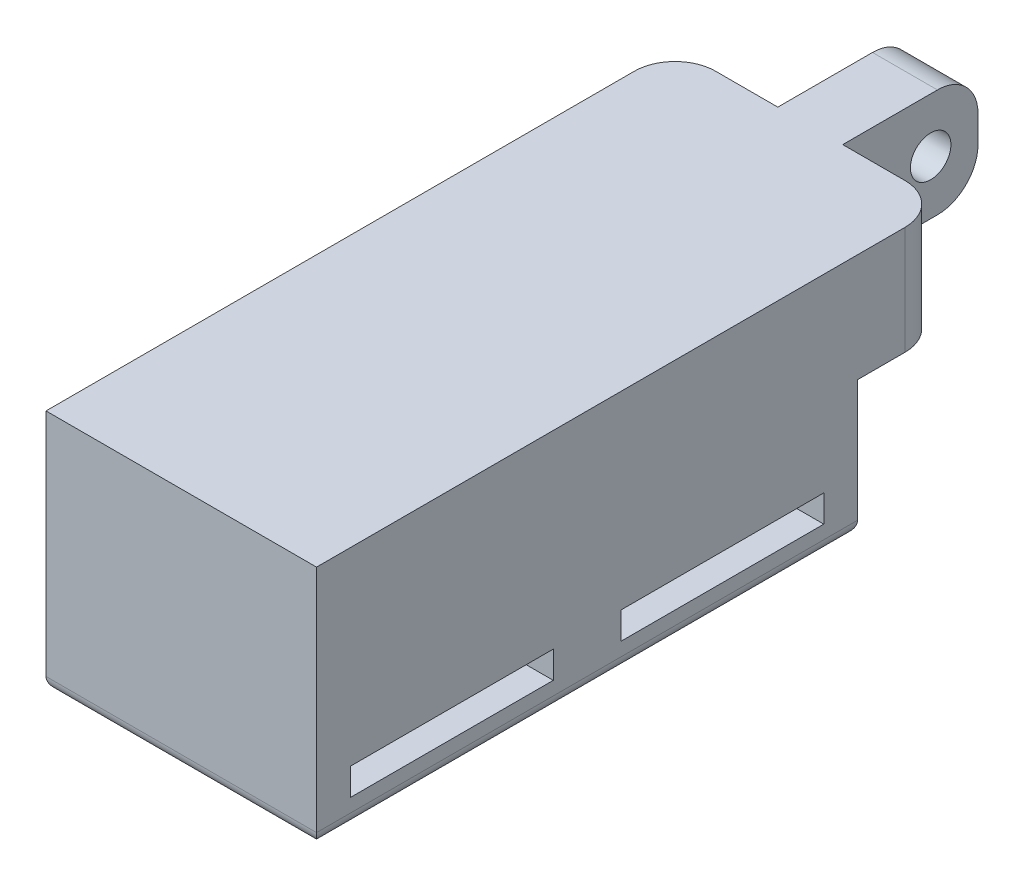
SolidWorks part; units mm, degrees
ref_plane "Alzado" through (0, 0, 0) normal (0, 0, 1) x (1, 0, 0)
ref_plane "Planta" through (0, 0, 0) normal (0, 1, 0) x (1, 0, 0)
ref_plane "Vista lateral" through (0, 0, 0) normal (1, 0, 0) x (0, 0, -1)
sketch "Croquis1" plane through (0, 0, 0) normal (1, 0, 0) x (0, 0, -1)
  line L0 (0, 9) -> (0, 1) construction
  line L9 (-1.5, 9) -> (-58, 9)
  line L18 (0, 9) -> (0, -9) construction
  line L19 (0, -9) -> (-58, -9) construction
  line L25 (0, 1) -> (-18, 1) construction
  line L26 (0, 1) -> (0, -2.6179) construction
  line L29 (0, -2.6179) -> (0, -9) construction
  line L31 (-1.5, 9) -> (-1.5, 1)
  line L32 (-18, 1) -> (-1.5, 1)
  line L35 (-58, -9) -> (-18, -9)
  line L56 (-58, 9) -> (-58, -9)
  line L59 (0, 9) -> (-58, 9) construction
  line L61 (-18, 1) -> (-18, -9)
  circle A0 centre (-5, 5) radius 1.5
  point P9 (0, 0)
  point P12 (0, 5)
  dimension "D6" = 3
  dimension "D1" = 58
  dimension "D2" = 10
  dimension "D3" = 40
  dimension "D4" = 8
  dimension "D7" = 5
  dimension "D8" = 3
extrude "Saliente-Extruir1" add sketch "Croquis1" along normal mid plane 20
sketch "Croquis2" plane through (0, 0, 0) normal (0, 1, 0) x (1, 0, 0)
  line L0 (-2.4, -11.5) -> (-10, -11.5)
  line L5 (10, -1.5) -> (-10, -1.5) construction
  line L7 (-10, -11.5) -> (-10, -1.5)
  line L8 (-2.4, -1.5) -> (2.4, -1.5) construction
  line L9 (-2.4, -1.5) -> (-2.4, -11.5)
  line L10 (-2.4, -11.5) -> (2.4, -11.5) construction
  line L11 (2.4, -1.5) -> (2.4, -11.5)
  line L12 (-10, -1.5) -> (-2.4, -1.5)
  line L13 (2.4, -11.5) -> (10, -11.5)
  line L15 (10, -11.5) -> (10, -1.5)
  line L16 (10, -1.5) -> (2.4, -1.5)
  line L17 (-10, -1.5) -> (-10, -58) construction
  line L18 (10, -1.5) -> (10, -58) construction
  point P6 (0, -1.5)
  dimension "D1" = 4.8
  dimension "D2" = 10
extrude "Cortar-Extruir1" cut sketch "Croquis2" against normal through all both and the other way through all
sketch "Croquis4" plane through (0, 0, 0) normal (1, 0, 0) x (0, 0, -1)
  line L0 (-58, -9) -> (-18, -9) construction
  line L1 (-55.5, -5) -> (-40.5, -5)
  line L2 (-55.5, -5) -> (-55.5, -7)
  line L3 (-55.5, -7) -> (-40.5, -7)
  line L4 (-40.5, -5) -> (-40.5, -7)
  line L5 (-55.5, -5) -> (-40.5, -7) construction
  line L6 (-55.5, -7) -> (-40.5, -5) construction
  line L7 (-18, -9) -> (-18, 1) construction
  line L8 (-35.5, -5) -> (-20.5, -5)
  line L9 (-35.5, -5) -> (-35.5, -7)
  line L10 (-35.5, -7) -> (-20.5, -7)
  line L11 (-20.5, -5) -> (-20.5, -7)
  line L12 (-58, 9) -> (-58, -9) construction
  point P0 (-48, -6)
  point P7 (-28, -7)
  point P16 (-48, -7)
  dimension "D1" = 2
  dimension "D2" = 2
  dimension "D3" = 15
  dimension "D4" = 10
  dimension "D5" = 10
extrude "Cortar-Extruir4" cut sketch "Croquis4" against normal through all both and the other way through all
fillet "Redondeo2" radius 1 4 edges at (10, -9, 38) (-10, -9, 38) (0, -9, 58) (0, -9, 18)
fillet "Redondeo3" radius 3 4 edges at (0, 1, 1.5) (-10, 5, 11.5) (10, 5, 11.5) (0, 9, 1.5)
